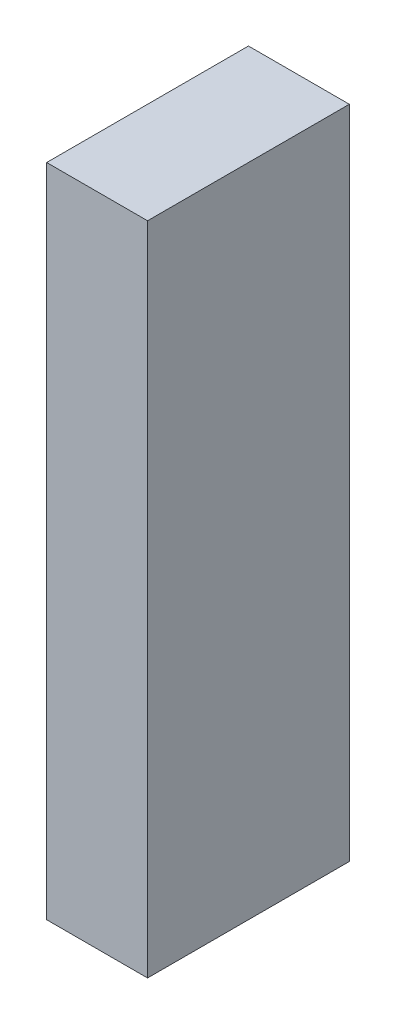
SolidWorks part; units mm, degrees
material "Pine"
ref_plane "Front Plane" through (0, 0, 0) normal (0, 0, 1) x (1, 0, 0)
ref_plane "Top Plane" through (0, 0, 0) normal (0, 1, 0) x (1, 0, 0)
ref_plane "Right Plane" through (0, 0, 0) normal (1, 0, 0) x (0, 0, -1)
sketch "Sketch1" plane through (0, 0, 0) normal (0, 1, 0) x (1, 0, 0)
  line L1 (0, 0) -> (50.8, 0)
  line L2 (0, 0) -> (0, 101.6)
  line L3 (0, 101.6) -> (50.8, 101.6)
  line L4 (50.8, 0) -> (50.8, 101.6)
  dimension "D1" = 50.8
  dimension "D2" = 101.6
extrude "Boss-Extrude1" add sketch "Sketch1" along normal blind 330.2
